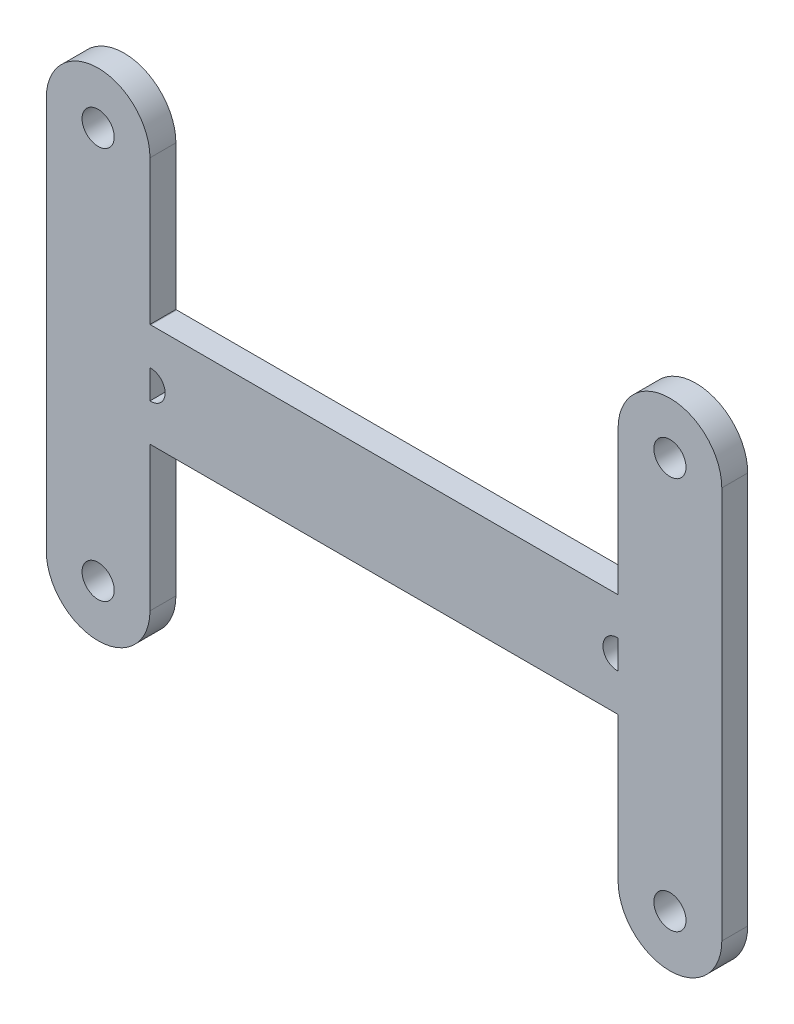
SolidWorks part; units mm, degrees
ref_plane "前视基准面" through (0, 0, 0) normal (0, 0, 1) x (1, 0, 0)
ref_plane "上视基准面" through (0, 0, 0) normal (0, 1, 0) x (1, 0, 0)
ref_plane "右视基准面" through (0, 0, 0) normal (1, 0, 0) x (0, 0, -1)
other "Configuration Table"
sketch "草图2" plane through (0, 0, 0) normal (0, 0, 1) x (1, 0, 0)
  line L16 (-27.5772, 18.9227) -> (-27.5772, -18.9227) construction
  line L17 (-22.5772, 18.9227) -> (-22.5772, -18.9227)
  line L18 (-32.5772, 18.9227) -> (-32.5772, -18.9227)
  line L19 (-27.5772, 0) -> (27.5772, 0) construction
  line L20 (0, 173.2407) -> (0, -173.2407) construction
  line L21 (27.5772, 18.9227) -> (27.5772, -18.9227) construction
  line L22 (22.5772, 18.9227) -> (22.5772, -18.9227)
  line L23 (32.5772, 18.9227) -> (32.5772, -18.9227)
  line L24 (-22.5, 0) -> (22.5, 0) construction
  line L25 (-22.5, 5) -> (22.5, 5)
  line L26 (-22.5, -5) -> (22.5, -5)
  arc A0 (-31.9865, -34.9731) -> (31.9865, -34.9731) centre (0, -46.4998) ccw construction
  arc A2 (-31.9865, -34.9731) -> (31.9865, -34.9731) centre (0, -46.4998) ccw construction
  arc A4 (31.9865, 34.9731) -> (-31.9865, 34.9731) centre (0, 46.4998) ccw construction
  arc A6 (31.9865, 34.9731) -> (-31.9865, 34.9731) centre (0, 46.4998) ccw construction
  arc A8 (-31.9865, -34.9731) -> (31.9865, -34.9731) centre (0, -46.4998) ccw
  arc A10 (-31.9865, -34.9731) -> (31.9865, -34.9731) centre (0, -46.4998) ccw
  arc A12 (31.9865, 34.9731) -> (-31.9865, 34.9731) centre (0, 46.4998) ccw
  arc A14 (31.9865, 34.9731) -> (-31.9865, 34.9731) centre (0, 46.4998) ccw
  circle A20 centre (27.5772, -18.9227) radius 1.55
  circle A21 centre (27.5772, 18.9227) radius 1.55
  circle A22 centre (-27.5772, -18.9227) radius 1.55
  circle A23 centre (-27.5772, 18.9227) radius 1.55
  arc A24 (-22.5772, 18.9227) -> (-32.5772, 18.9227) centre (-27.5772, 18.9227) ccw
  arc A25 (-32.5772, -18.9227) -> (-22.5772, -18.9227) centre (-27.5772, -18.9227) ccw
  circle A26 centre (-22.5, 0) radius 1.3849
  circle A28 centre (22.5, 0) radius 1.3849
  arc A29 (22.5772, 18.9227) -> (32.5772, 18.9227) centre (27.5772, 18.9227) cw
  arc A30 (32.5772, -18.9227) -> (22.5772, -18.9227) centre (27.5772, -18.9227) cw
  arc A31 (-22.5, 5) -> (-22.5, -5) centre (-22.5, 0) ccw
  arc A32 (22.5, -5) -> (22.5, 5) centre (22.5, 0) ccw
  point P34 (-27.5772, 0)
  point P50 (27.5772, 0)
  point P55 (0, 0)
  dimension "D1" = 10
  dimension "D2" = 22.5
extrude "凸台-拉伸1" add sketch "草图2" along normal blind 2.5
